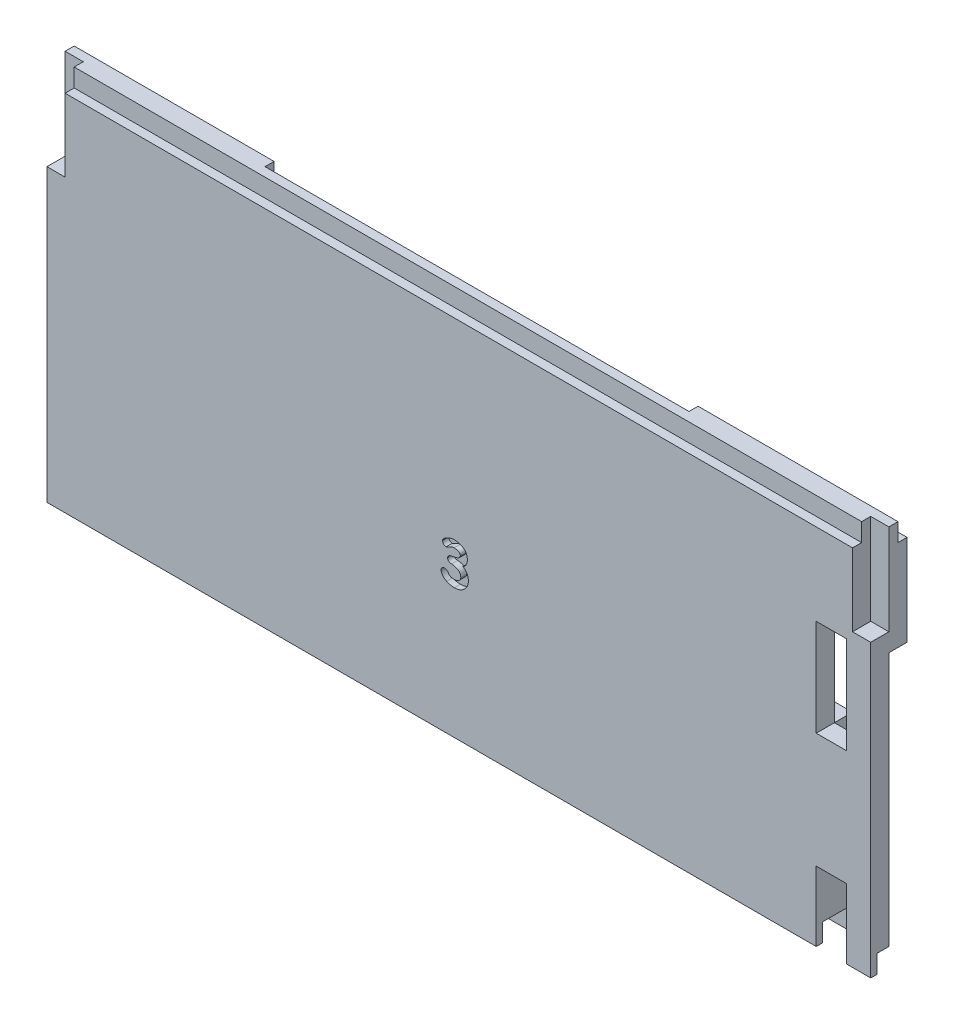
SolidWorks part; units mm, degrees
material "ABS"
ref_plane "前基準面" through (0, 0, 0) normal (0, 0, 1) x (1, 0, 0)
ref_plane "上基準面" through (0, 0, 0) normal (0, 1, 0) x (1, 0, 0)
ref_plane "右基準面" through (0, 0, 0) normal (1, 0, 0) x (0, 0, -1)
sketch "草圖1" plane through (0, 0, 0) normal (0, 0, 1) x (1, 0, 0)
  line L1 (-57.6613, 31.8683) -> (72.3387, 31.8683)
  line L2 (-57.6613, 31.8683) -> (-57.6613, -28.1317)
  line L3 (-57.6613, -28.1317) -> (72.3387, -28.1317)
  line L4 (72.3387, 31.8683) -> (72.3387, -28.1317)
  dimension "D1" = 130
  dimension "D2" = 60
extrude "填料-伸長1" add sketch "草圖1" along normal blind 6
sketch "草圖2" plane through (-57.6613, 0, 0) normal (-1, 0, 0) x (0, 0, 1)
  line L0 (6, -28.1317) -> (0, -28.1317) construction
  line L1 (3, -28.1317) -> (6, -28.1317)
  line L2 (3, -28.1317) -> (3, 19.8683)
  line L3 (3, 19.8683) -> (6, 19.8683)
  line L4 (6, -28.1317) -> (6, 19.8683)
  line L5 (6, 31.8683) -> (6, -28.1317) construction
  line L7 (0, 31.8683) -> (3, 31.8683)
  line L8 (0, 31.8683) -> (0, 16.8683)
  line L9 (0, 16.8683) -> (3, 16.8683)
  line L10 (3, 31.8683) -> (3, 16.8683)
  line M3 (0, 31.8683) -> (0, -28.1317)
  line M4 (0, -28.1317) -> (6, -28.1317)
  line M5 (6, -28.1317) -> (6, 31.8683)
  line M6 (6, 31.8683) -> (0, 31.8683)
  dimension "D1" = 45
  dimension "D2" = 3
extrude "填料-伸長2" add sketch "草圖2" along normal blind 3 and the other way blind 133 contours L3 L2 M4 M5 | L10 L9 L2 M6 M3
sketch "草圖3" plane through (0, -28.1317, 0) normal (0, -1, 0) x (1, 0, 0)
  line L1 (-60.6613, 5) -> (77.8984, 5)
  line L2 (-60.6613, 5) -> (-60.6613, 1)
  line L3 (-60.6613, 1) -> (77.8984, 1)
  line L4 (77.8984, 5) -> (77.8984, 1)
  line L5 (-60.6613, 6) -> (75.3387, 6) construction
  point P6 (0, 0)
  dimension "D1" = 4
  dimension "D2" = 1
extrude "除料-伸長1" cut sketch "草圖3" against normal blind 3
sketch "草圖4" plane through (0, 31.8683, 0) normal (0, 1, 0) x (1, 0, 0)
  line L0 (-57.6613, -6) -> (-57.6613, -3) construction
  line L1 (-57.6613, -4.5) -> (72.3387, -4.5)
  line L2 (-57.6613, -4.5) -> (-57.6613, -3)
  line L3 (-57.6613, -3) -> (72.3387, -3)
  line L4 (72.3387, -4.5) -> (72.3387, -3)
  line L5 (75.3387, -3) -> (75.3387, 0) construction
  line L6 (75.3387, -1.5) -> (-60.6613, -1.5)
  line L7 (75.3387, -1.5) -> (75.3387, -3)
  line L8 (75.3387, -3) -> (-60.6613, -3)
  line L9 (-60.6613, -1.5) -> (-60.6613, -3)
  line M2 (-60.6613, 0) -> (-60.6613, -3)
  line M3 (-60.6613, -3) -> (-57.6613, -3)
  line M4 (-57.6613, -3) -> (-57.6613, -6)
  line M6 (72.3387, -6) -> (72.3387, -3)
  line M7 (72.3387, -3) -> (75.3387, -3)
  line M8 (75.3387, -3) -> (75.3387, 0)
extrude "填料-伸長3" add sketch "草圖4" along normal blind 3 contours L6 L3 M8 M2 M3 M7 | L3 L1 M4 M6
sketch "草圖5" plane through (0, 0, 6) normal (0, 0, 1) x (1, 0, 0)
  line L0 (-60.6613, -28.1317) -> (75.3387, -28.1317) construction
  line L1 (71.3387, -28.1317) -> (66.3387, -28.1317)
  line L2 (71.3387, -28.1317) -> (71.3387, -16.6317)
  line L3 (71.3387, -16.6317) -> (66.3387, -16.6317)
  line L4 (66.3387, -28.1317) -> (66.3387, -16.6317)
  line L5 (75.3387, -28.1317) -> (75.3387, 19.8683) construction
  line L7 (71.3387, 2.3683) -> (66.3387, 2.3683)
  line L8 (71.3387, 2.3683) -> (71.3387, 18.3683)
  line L9 (71.3387, 18.3683) -> (66.3387, 18.3683)
  line L10 (66.3387, 2.3683) -> (66.3387, 18.3683)
  dimension "D1" = 11.5
  dimension "D2" = 5
  dimension "D3" = 4
  dimension "D4" = 30.5
  dimension "D5" = 16
  dimension "D6" = 5
  dimension "D7" = 4
extrude "除料-伸長3" cut sketch "草圖5" against normal through all
sketch "草圖6" plane through (0, 0, 0) normal (0, 0, -1) x (-1, 0, 0)
  line L1 (-42.3387, 53.9204) -> (27.6613, 53.9204)
  line L2 (-42.3387, 53.9204) -> (-42.3387, -28.1317)
  line L3 (-42.3387, -28.1317) -> (27.6613, -28.1317)
  line L4 (27.6613, 53.9204) -> (27.6613, -28.1317)
  line L5 (57.6613, -28.1317) -> (-66.3387, -28.1317) construction
  line L6 (-72.3387, -28.1317) -> (-72.3387, 16.8683) construction
  line L7 (57.6613, 16.8683) -> (57.6613, -25.1317) construction
  line L9 (-66.3387, 18.3683) -> (-42.3387, 18.3683)
  line L10 (-66.3387, 18.3683) -> (-66.3387, 2.3683)
  line L11 (-66.3387, 2.3683) -> (-42.3387, 2.3683)
  line L12 (-42.3387, 18.3683) -> (-42.3387, 2.3683)
  line M9 (-66.3387, -28.1317) -> (57.6613, -28.1317)
  line M13 (60.6613, 31.8683) -> (-75.3387, 31.8683)
  line M20 (-66.3387, 18.3683) -> (-66.3387, 2.3683)
  dimension "D1" = 30
  dimension "D2" = 30
extrude "除料-伸長4" cut sketch "草圖6" against normal blind 3 contours L11 L2 L9 M20 | L4 L2 M13 M9 | L4 L1 L2 M13
sketch "草圖7" plane through (0, 0, 0) normal (0, 0, -1) x (-1, 0, 0)
  line L1 (-71.3387, 2.3683) -> (-66.3387, 2.3683)
  line L2 (-71.3387, 2.3683) -> (-71.3387, -16.6317)
  line L3 (-71.3387, -16.6317) -> (-66.3387, -16.6317)
  line L4 (-66.3387, 2.3683) -> (-66.3387, -16.6317)
extrude "除料-伸長5" cut sketch "草圖7" against normal blind 3
sketch "草圖8" plane through (0, 0, 6) normal (0, 0, 1) x (1, 0, 0)
  text T0 "3" font "Comic Sans MS" height in points 24
extrude "除料-伸長6" cut sketch "草圖8" against normal blind 1
